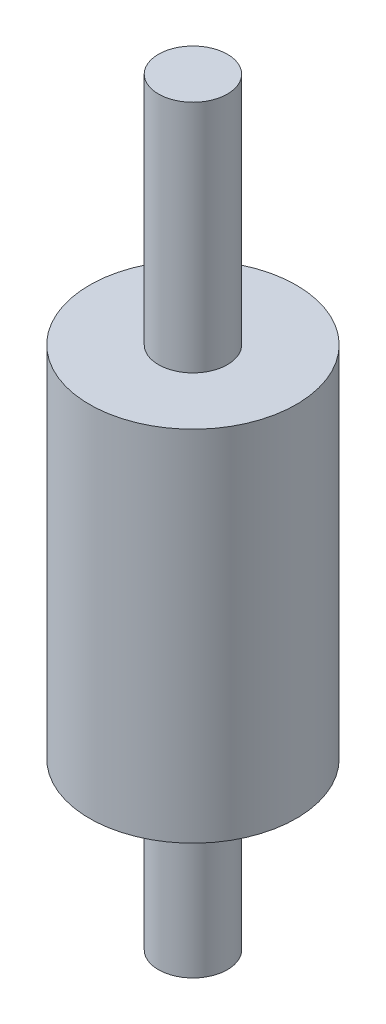
SolidWorks part; units mm, degrees
ref_plane "Front Plane" through (0, 0, 0) normal (0, 0, 1) x (1, 0, 0)
ref_plane "Top Plane" through (0, 0, 0) normal (0, 1, 0) x (1, 0, 0)
ref_plane "Right Plane" through (0, 0, 0) normal (1, 0, 0) x (0, 0, -1)
sketch "Sketch1" plane through (0, 0, 0) normal (1, 0, 0) x (0, 0, -1)
  line L0 (0, -27.5) -> (2.5, -27.5)
  line L1 (2.5, -27.5) -> (2.5, -15.5)
  line L2 (2.5, -15.5) -> (7.5, -15.5)
  line L3 (7.5, -15.5) -> (7.5, 10.5)
  line L4 (7.5, 10.5) -> (2.5, 10.5)
  line L5 (2.5, 10.5) -> (2.5, 27.5)
  line L6 (2.5, 27.5) -> (0, 27.5)
  line L7 (0, 27.5) -> (0, -27.5)
  line L8 (0, 0) -> (0, 62.5912) construction
  dimension "D1" = 26
  dimension "D2" = 5
  dimension "D3" = 5
  dimension "D4" = 15
  dimension "D5" = 17
  dimension "D6" = 12
revolve "Revolve1" add sketch "Sketch1" angle 360 about L8
cosmetic thread "Cosmetic Thread1" parameters "D2"=3.22
cosmetic thread "Cosmetic Thread2" parameters "D2"=3.22
